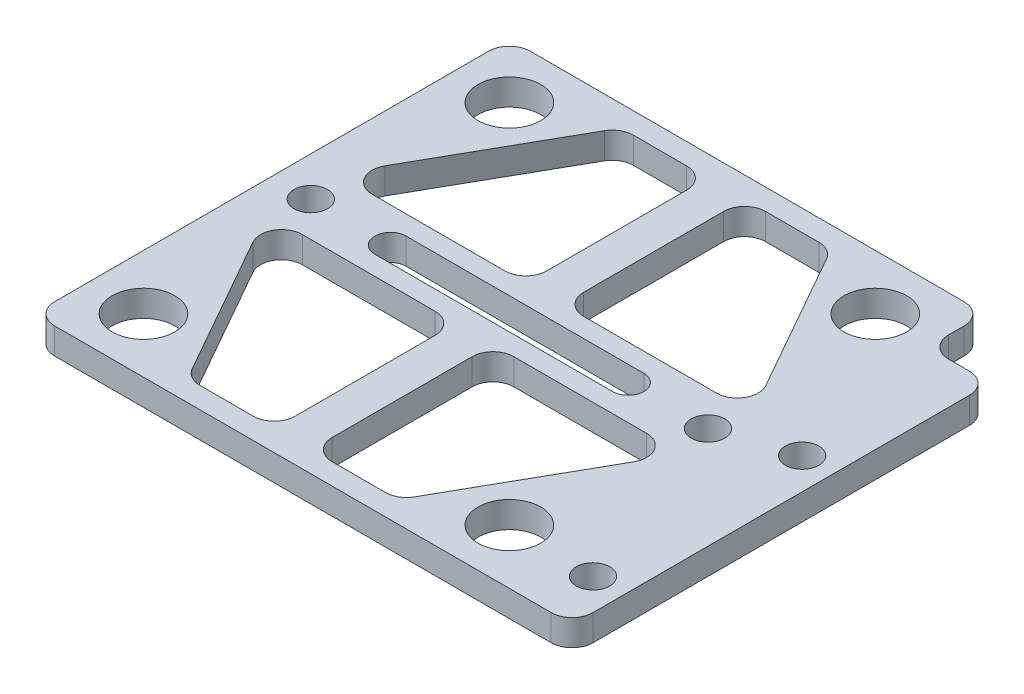
SolidWorks part; units mm, degrees
material "A-玻璃纤维"
ref_plane "前视基准面" through (0, 0, 0) normal (0, 0, 1) x (1, 0, 0)
ref_plane "上视基准面" through (0, 0, 0) normal (0, 1, 0) x (1, 0, 0)
ref_plane "右视基准面" through (0, 0, 0) normal (1, 0, 0) x (0, 0, -1)
sketch "草图1" plane through (0, 0, 0) normal (0, 1, 0) x (1, 0, 0)
  line L0 (0, 0) -> (0, 17.5) construction
  line L1 (-17.5, 17.5) -> (17.5, 17.5) construction
  line L2 (-17.5, 17.5) -> (-17.5, -17.5) construction
  line L3 (-17.5, -17.5) -> (17.5, -17.5) construction
  line L4 (17.5, 17.5) -> (17.5, -17.5) construction
  line L5 (-17.5, 17.5) -> (17.5, -17.5) construction
  line L6 (-17.5, -17.5) -> (17.5, 17.5) construction
  line L8 (-22.75, 22.75) -> (22.75, 22.75)
  line L9 (-22.75, 22.75) -> (-22.75, -22.75)
  line L10 (-22.75, -22.75) -> (22.75, -22.75)
  line L11 (22.75, 22.75) -> (22.75, -22.75)
  line L12 (-22.75, 22.75) -> (22.75, -22.75) construction
  line L13 (-22.75, -22.75) -> (22.75, 22.75) construction
  circle A0 centre (17.5, 17.5) radius 3
  circle A1 centre (17.5, -17.5) radius 3
  circle A2 centre (-17.5, -17.5) radius 3
  circle A3 centre (-17.5, 17.5) radius 3
  point P0 (0, 0)
  dimension "D2" = 6
  dimension "D1" = 35
  dimension "D3" = 45.5
extrude "凸台-拉伸1" add sketch "草图1" along normal blind 2.5
sketch "草图2" plane through (0, 2.5, 0) normal (0, 1, 0) x (1, 0, 0)
  line L0 (22.75, -22.75) -> (22.75, 22.75) construction
  line L1 (22.75, -22.75) -> (22.75, 17.25)
  line L2 (22.75, 17.25) -> (28.75, 17.25)
  line L3 (28.75, 17.25) -> (28.75, -22.75)
  line L4 (28.75, -22.75) -> (22.75, -22.75)
  line L5 (25.75, -22.75) -> (25.75, 17.25) construction
  circle A0 centre (25.75, -17.75) radius 1.6
  circle A1 centre (25.75, 2.25) radius 1.6
  dimension "D3" = 3.2
  dimension "D4" = 20
  dimension "D5" = 5
  dimension "D1" = 6
  dimension "D2" = 40
extrude "凸台-拉伸2" add sketch "草图2" against normal up to surface (2.5 mm away) up to face at (0, 0, 0)
fillet "圆角1" radius 2 6 edges at (22.75, 1.25, -22.75) (-22.75, 1.25, -22.75) (-22.75, 1.25, 22.75) (28.75, 1.25, 22.75) (28.75, 1.25, -17.25) (22.75, 1.25, -17.25)
sketch "草图3" plane through (0, 2.5, 0) normal (0, 1, 0) x (1, 0, 0)
  line L0 (0, 0) -> (0, 22.75) construction
  line L1 (20.75, 22.75) -> (-20.75, 22.75) construction
  line L2 (0, 0) -> (-22.75, 0) construction
  line L3 (-22.75, 20.75) -> (-22.75, -20.75) construction
  line L4 (-10.046, 20.7293) -> (-19.8939, 3.337)
  line L5 (-19.8939, 3.337) -> (-1.7668, 3.337)
  line L6 (-1.7668, 3.337) -> (-1.7668, 20.7293)
  line L7 (-1.7668, 20.7293) -> (-10.046, 20.7293)
  line L8 (1.7668, 3.337) -> (1.7668, 20.7293)
  line L9 (19.8939, 3.337) -> (1.7668, 3.337)
  line L10 (10.046, 20.7293) -> (19.8939, 3.337)
  line L11 (1.7668, 20.7293) -> (10.046, 20.7293)
  line L12 (19.8939, -3.337) -> (1.7668, -3.337)
  line L13 (10.046, -20.7293) -> (19.8939, -3.337)
  line L14 (1.7668, -20.7293) -> (10.046, -20.7293)
  line L15 (1.7668, -3.337) -> (1.7668, -20.7293)
  line L16 (-1.7668, -3.337) -> (-1.7668, -20.7293)
  line L17 (-19.8939, -3.337) -> (-1.7668, -3.337)
  line L18 (-10.046, -20.7293) -> (-19.8939, -3.337)
  line L19 (-1.7668, -20.7293) -> (-10.046, -20.7293)
  line L20 (-11.375, 0) -> (11.375, 0) construction
  line L21 (-11.375, 1.5) -> (11.375, 1.5)
  line L22 (-11.375, -1.5) -> (11.375, -1.5)
  arc A0 (-11.375, 1.5) -> (-11.375, -1.5) centre (-11.375, 0) ccw
  arc A1 (11.375, -1.5) -> (11.375, 1.5) centre (11.375, 0) ccw
  point P26 (0, 0)
  dimension "D1" = 1.5
extrude "切除-拉伸1" cut sketch "草图3" against normal through all
fillet "圆角2" radius 2 16 edges at (-1.7668, 1.25, -3.337) (-19.8939, 1.25, -3.337) (-1.7668, 1.25, -20.7293) (1.7668, 1.25, -20.7293) (10.046, 1.25, -20.7293) (19.8939, 1.25, -3.337) (1.7668, 1.25, -3.337) (1.7668, 1.25, 20.7293) (1.7668, 1.25, 3.337) (19.8939, 1.25, 3.337) (10.046, 1.25, 20.7293) (-1.7668, 1.25, 20.7293) (-10.046, 1.25, 20.7293) (-19.8939, 1.25, 3.337) (-1.7668, 1.25, 3.337) (-10.046, 1.25, -20.7293)
sketch "草图4" plane through (0, 2.5, 0) normal (0, 1, 0) x (1, 0, 0)
  line L0 (0, 0) -> (0, 22.75) construction
  line L1 (20.75, 22.75) -> (-20.75, 22.75) construction
  line L2 (0, 0) -> (-19, 0) construction
  circle A0 centre (-19, 0) radius 1.6
  circle A1 centre (19, 0) radius 1.6
  dimension "D1" = 3.2
  dimension "D2" = 38
extrude "切除-拉伸2" cut sketch "草图4" against normal through all
